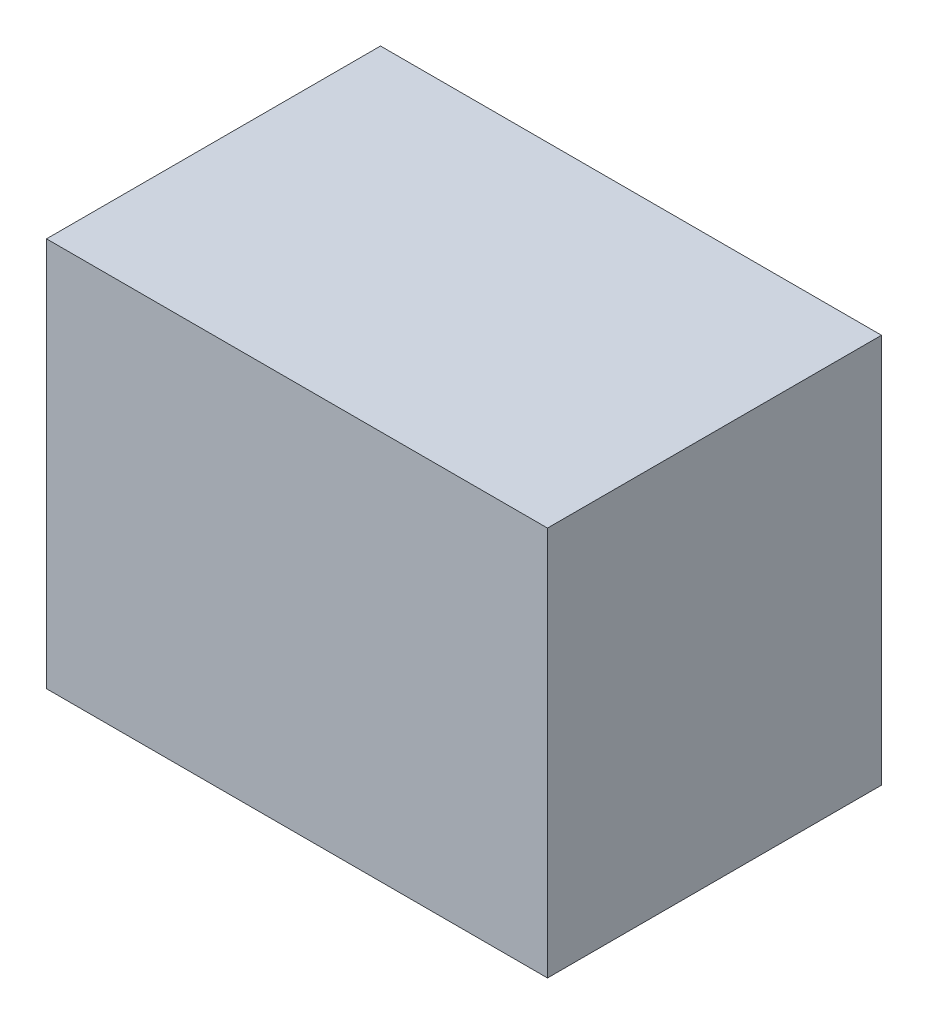
SolidWorks part; units mm, degrees
ref_plane "前视基准面" through (0, 0, 0) normal (0, 0, 1) x (1, 0, 0)
ref_plane "上视基准面" through (0, 0, 0) normal (0, 1, 0) x (1, 0, 0)
ref_plane "右视基准面" through (0, 0, 0) normal (1, 0, 0) x (0, 0, -1)
other "Configuration Table"
sketch "草图1" plane through (0, 0, 0) normal (0, 0, 1) x (1, 0, 0)
  line L1 (-45, -35) -> (45, -35)
  line L2 (-45, -35) -> (-45, 35)
  line L3 (-45, 35) -> (45, 35)
  line L4 (45, -35) -> (45, 35)
  line L5 (-45, -35) -> (45, 35) construction
  line L6 (-45, 35) -> (45, -35) construction
  point P0 (0, 0)
extrude "凸台-拉伸1" add sketch "草图1" along normal blind 60
